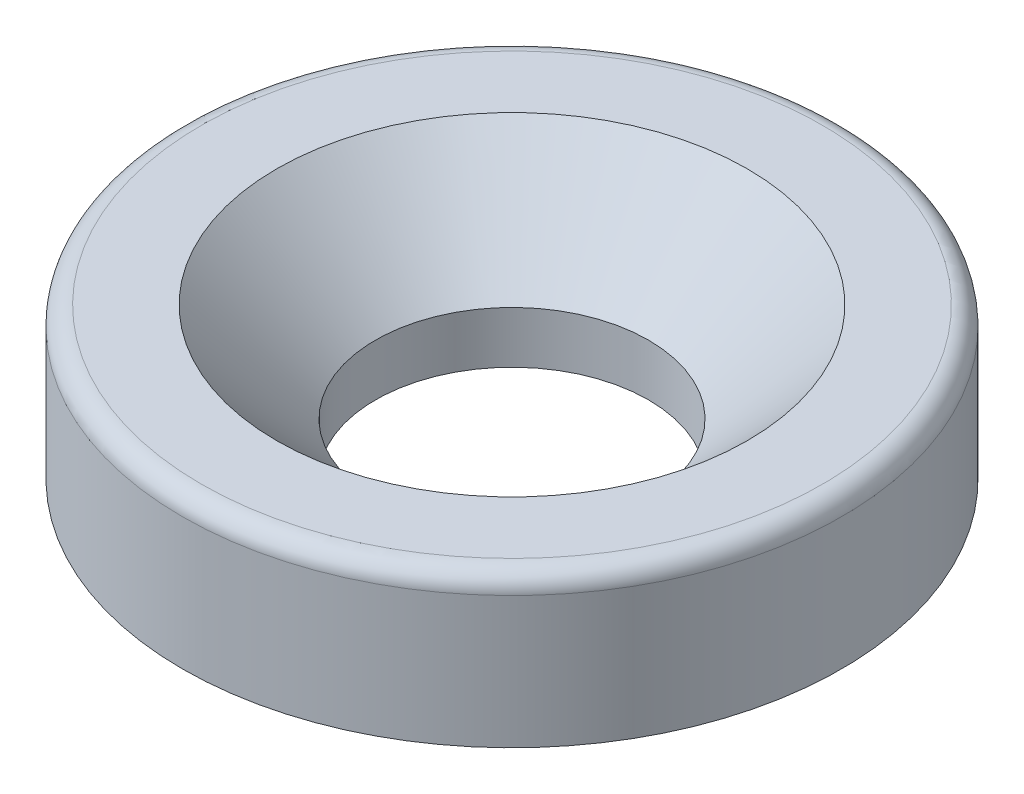
SolidWorks part; units mm, degrees
material "Plain Carbon Steel"
ref_plane "Front Plane" through (0, 0, 0) normal (0, 0, 1) x (1, 0, 0)
ref_plane "Top Plane" through (0, 0, 0) normal (0, 1, 0) x (1, 0, 0)
ref_plane "Right Plane" through (0, 0, 0) normal (1, 0, 0) x (0, 0, -1)
sketch "Sketch1" plane through (0, 0, 0) normal (0, 0, 1) x (1, 0, 0)
  line L1 (0, 0) -> (17.5, 0)
  line L2 (0, 0) -> (0, 8)
  line L3 (0, 8) -> (17.5, 8)
  line L4 (17.5, 0) -> (17.5, 8)
  dimension "D1" = 17.5
  dimension "D2" = 8
revolve "Revolve1" add sketch "Sketch1" angle 360 about L2
hole_wizard "CSK for M3 Countersunk Flat Head Screw1" positions "3DSketch1" profile "Sketch2" countersink size "M3" standard "ISO" end condition through all
sketch3d "3DSketch1"
  line L0 (0, 8, 0) -> (0, 0, 0) construction
  point P0 (0, 8, 0)
  point P5 (0, 0, 0)
sketch "Sketch2" plane through (0, 8, 0) normal (1, 0, 0) x (0, 0, 1)
  line L0 (0, 0) -> (0, 8)
  line L1 (0, 8) -> (7.25, 8)
  line L2 (7.25, 8) -> (7.25, 5.25)
  line L3 (7.25, 5.25) -> (12.5, 0)
  line L5 (12.5, 0) -> (0, 0)
  line L6 (-7.25, 5.25) -> (-12.5, 0) construction
  line L11 (0, -6.35) -> (0, 107.95) construction
  dimension "Thru Hole Dia." = 14.5
  dimension "Thru Hole Depth" = 8
  dimension "Near C'Sink Dia." = 25
  dimension "Near C'Sink Angle" = 90
fillet "Fillet1" radius 1 1 edges at (0, 8, -17.5)
